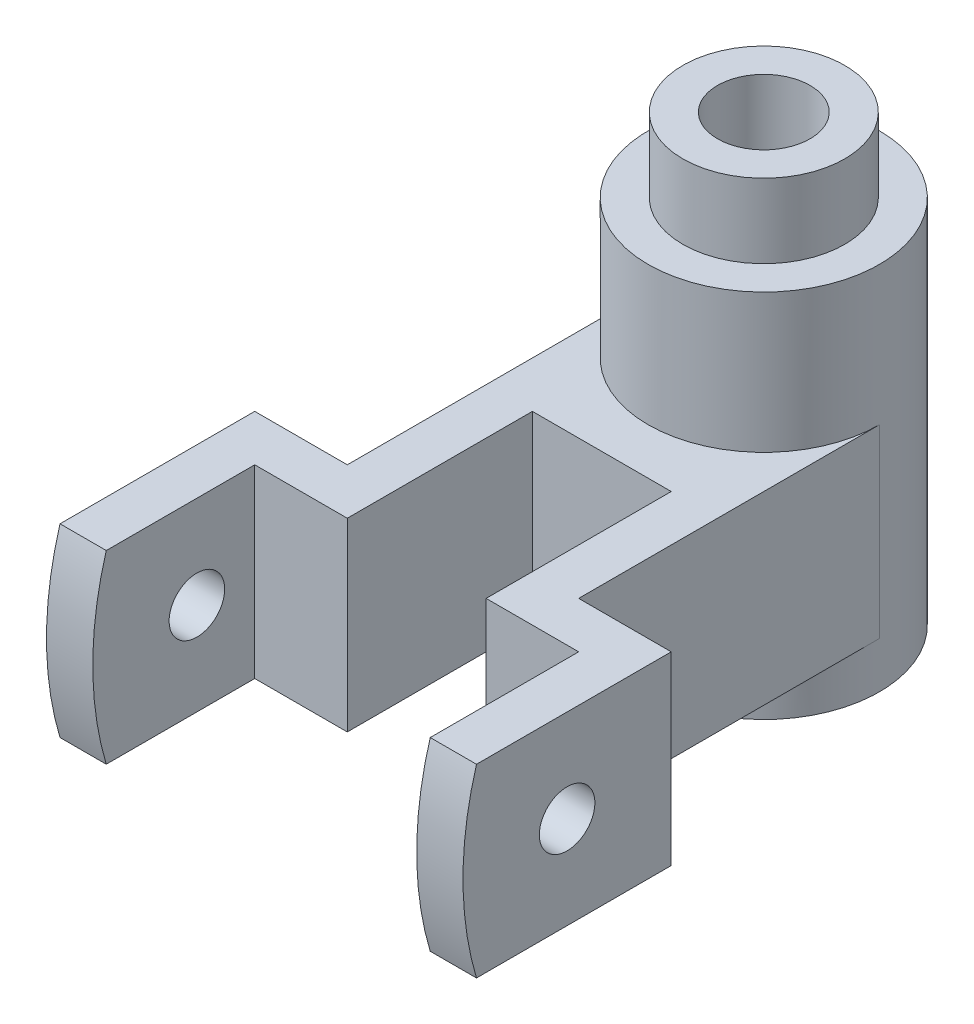
SolidWorks part; units mm, degrees
ref_plane "Front Plane" through (0, 0, 0) normal (0, 0, 1) x (1, 0, 0)
ref_plane "Top Plane" through (0, 0, 0) normal (0, 1, 0) x (1, 0, 0)
ref_plane "Right Plane" through (0, 0, 0) normal (1, 0, 0) x (0, 0, -1)
sketch "Sketch1" plane through (0, 0, 0) normal (0, 1, 0) x (1, 0, 0)
  circle A0 centre (0, 0) radius 25
  dimension "D1" = 50
extrude "Boss-Extrude1" add sketch "Sketch1" along normal blind 80
sketch "Sketch2" plane through (0, 80, 0) normal (0, 1, 0) x (1, 0, 0)
  circle A0 centre (0, 0) radius 17.5
  dimension "D1" = 35
extrude "Boss-Extrude2" add sketch "Sketch2" along normal blind 16
sketch "Sketch3" plane through (0, 96, 0) normal (0, 1, 0) x (1, 0, 0)
  circle A0 centre (0, 0) radius 10
  dimension "D1" = 20
extrude "Cut-Extrude1" cut sketch "Sketch3" against normal blind 144
ref_plane "Plane2" through (0, 50, 0) normal (0, 1, 0) x (1, 0, 0)
sketch "Sketch4" plane through (0, 50, 0) normal (0, 1, 0) x (1, 0, 0)
  line L0 (0, 0) -> (0, -35)
  line L1 (-25, 0) -> (25, 0)
  line L2 (-25, 0) -> (-25, -65)
  line L3 (-25, -65) -> (25, -65)
  line L4 (25, 0) -> (25, -65)
  line L5 (0, -35) -> (-15, -35)
  line L7 (-15, -35) -> (15, -35)
  line L8 (-15, -35) -> (-15, -65)
  line L9 (-15, -65) -> (15, -65)
  line L10 (15, -35) -> (15, -65)
  circle A0 centre (0, 0) radius 25 construction
  dimension "D1" = 65
  dimension "D2" = 35
  dimension "D3" = 15
  dimension "D4" = 30
extrude "Boss-Extrude3" add sketch "Sketch4" against normal blind 40 contours L8 L5 L0 L1 L2 L3 | L7 L10 L3 L4 L1 L0
sketch "Sketch5" plane through (0, 0, 65) normal (0, 0, 1) x (1, 0, 0)
  line L0 (0, 10) -> (0, 50)
  line L1 (15, 10) -> (-15, 10) construction
  line L2 (27.5, 50) -> (-27.5, 50) construction
  line L4 (-45, 10) -> (45, 10)
  line L5 (-45, 10) -> (-45, 50)
  line L6 (-45, 50) -> (45, 50)
  line L7 (45, 10) -> (45, 50)
  line L8 (-45, 10) -> (45, 50) construction
  line L9 (-45, 50) -> (45, 10) construction
  line L10 (-15, 10) -> (15, 10)
  line L11 (-15, 10) -> (-15, 50)
  line L12 (-15, 50) -> (15, 50)
  line L13 (15, 10) -> (15, 50)
  line L14 (-15, 10) -> (15, 50) construction
  line L15 (-15, 50) -> (15, 10) construction
  point P7 (0, 30)
  point P12 (0, 30)
  line M4 (25, 50) -> (15, 50)
  line M5 (15, 50) -> (15, 10)
  line M6 (15, 10) -> (25, 10)
  line M7 (25, 10) -> (25, 50)
  dimension "D1" = 90
  dimension "D2" = 30
  dimension "D3" = 40
extrude "Boss-Extrude4" add sketch "Sketch5" along normal blind 10 contours L4 L11 L6 L5 | L4 L7 L6 M7 | M7 M4 M5 M6
sketch "Sketch6" plane through (0, 0, 75) normal (0, 0, 1) x (1, 0, 0)
  line L1 (-45, 50) -> (-35, 50)
  line L2 (-45, 50) -> (-45, 10)
  line L3 (-45, 10) -> (-35, 10)
  line L4 (-35, 50) -> (-35, 10)
  dimension "D1" = 40
  dimension "D2" = 10
extrude "Boss-Extrude5" add sketch "Sketch6" along normal blind 35
sketch "Sketch7" plane through (-35, 0, 0) normal (1, 0, 0) x (0, 0, -1)
  line L0 (-110, 50) -> (-110, 10)
  line L1 (-110, 10) -> (-75, 10) construction
  line L2 (-110, 10) -> (-110, 50) construction
  line L3 (-110, 30) -> (-40, 30)
  line L4 (-110, 30) -> (-87.5, 30)
  line L5 (-110, 50) -> (-75, 50)
  line L6 (-110, 50) -> (-110, 10)
  line L7 (-110, 10) -> (-75, 10)
  line L8 (-75, 50) -> (-75, 10)
  circle A0 centre (-40, 30) radius 70
  circle A1 centre (-87.5, 30) radius 6
  line M9 (-110, 50) -> (-110, 10)
  line M10 (-110, 10) -> (-75, 10)
  dimension "D3" = 12
  dimension "D1" = 70
  dimension "D2" = 22.5
extrude "Cut-Extrude2" cut sketch "Sketch7" against normal blind 35 contours A0 L5 M9 | A0 L0 M10 | L4 A1 L3 | L3 A1 L4
mirror "Mirror1" about plane through (0, 0, 0) normal (1, 0, 0) of "Cut-Extrude2", "Boss-Extrude5"
